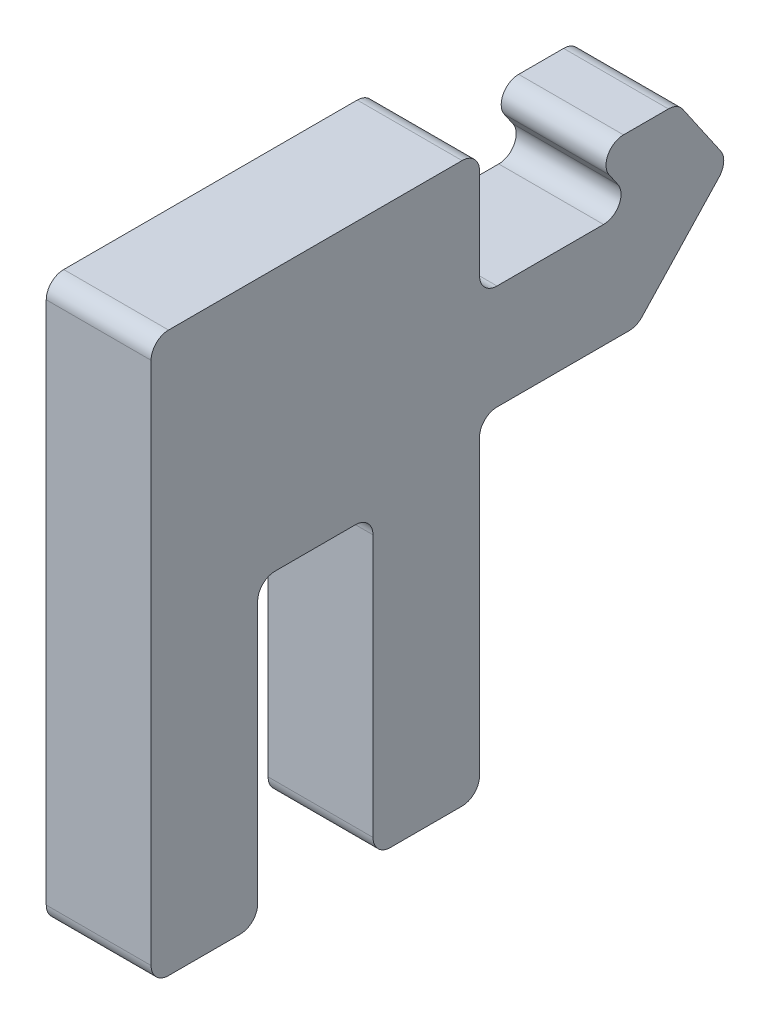
SolidWorks part; units mm, degrees
ref_plane "Alzado" through (0, 0, 0) normal (0, 0, 1) x (1, 0, 0)
ref_plane "Planta" through (0, 0, 0) normal (0, 1, 0) x (1, 0, 0)
ref_plane "Vista lateral" through (0, 0, 0) normal (1, 0, 0) x (0, 0, -1)
sketch "Croquis1" plane through (0, 0, 0) normal (1, 0, 0) x (0, 0, -1)
  line L1 (-4.7, 8) -> (4.7, 8)
  line L2 (-4.7, 8) -> (-4.7, -8)
  line L3 (-4.7, -8) -> (4.7, -8)
  line L16 (4.7, 8) -> (4.7, -8)
  dimension "D1" = 4.7
  dimension "D2" = 8
  dimension "D3" = 16
  dimension "D4" = 9.4
extrude "Saliente-Extruir1" add sketch "Croquis1" along normal blind 3
sketch "Croquis2" plane through (3, 0, 0) normal (1, 0, 0) x (0, 0, -1)
  line L0 (0, 0) -> (0, -9.3656) construction
  line L1 (-4.7, -8) -> (4.7, -8) construction
  line L2 (-1.65, -8) -> (1.65, -8)
  line L3 (-1.65, -8) -> (-1.65, 0.5)
  line L4 (-1.65, 0.5) -> (1.65, 0.5)
  line L5 (1.65, -8) -> (1.65, 0.5)
  point P9 (0, -8)
  dimension "D1" = 3.3
  dimension "D3" = 8.5
extrude "Cortar-Extruir1" cut sketch "Croquis2" against normal up to surface (3 mm away) up to face at (0, 0, 0)
sketch "Croquis4" plane through (3, 0, 0) normal (1, 0, 0) x (0, 0, -1)
  line L9 (1.65, 0.5) -> (-1.65, 0.5) construction
  line L10 (0, 0.5) -> (0, 10.8389) construction
  line L18 (4.7, 4.3918) -> (4.7, 1.3918)
  line L19 (4.7, -8) -> (4.7, 8) construction
  line L20 (4.7, 1.3918) -> (9.2, 1.3918)
  line L22 (9.2, 4.3918) -> (4.7, 4.3918)
  line L25 (7.8691, 6.3274) -> (9.2, 4.3918)
  line L26 (7.8691, 6.3274) -> (10.3691, 6.3274)
  line L27 (10.3691, 6.3274) -> (11.8287, 4.2046)
  line L28 (11.8287, 4.2046) -> (9.2, 1.3918)
  dimension "D1" = 4.5
  dimension "D2" = 3
  dimension "D3" = 4.5
  dimension "D4" = 3.8918
  dimension "D5" = 5.8274
  dimension "D6" = 6.1126
  dimension "D7" = 2.5
  dimension "D8" = 11.8459
extrude "Saliente-Extruir2" add sketch "Croquis4" against normal up to surface (3 mm away) up to face at (0, -1.875, 0)
fillet "Redondeo1" radius 0.5 15 edges at (1.5, 8, 4.7) (1.5, 4.3918, -4.7) (1.5, 8, -4.7) (1.5, 6.3274, -7.8691) (1.5, 6.3274, -10.3691) (1.5, 4.2046, -11.8287) (1.5, 1.3918, -9.2) (1.5, 1.3918, -4.7) (1.5, 0.5, -1.65) (1.5, 0.5, 1.65) (1.5, -8, 1.65) (1.5, -8, 4.7) (1.5, -8, -4.7) (1.5, -8, -1.65) (1.5, 4.3918, -9.2)
